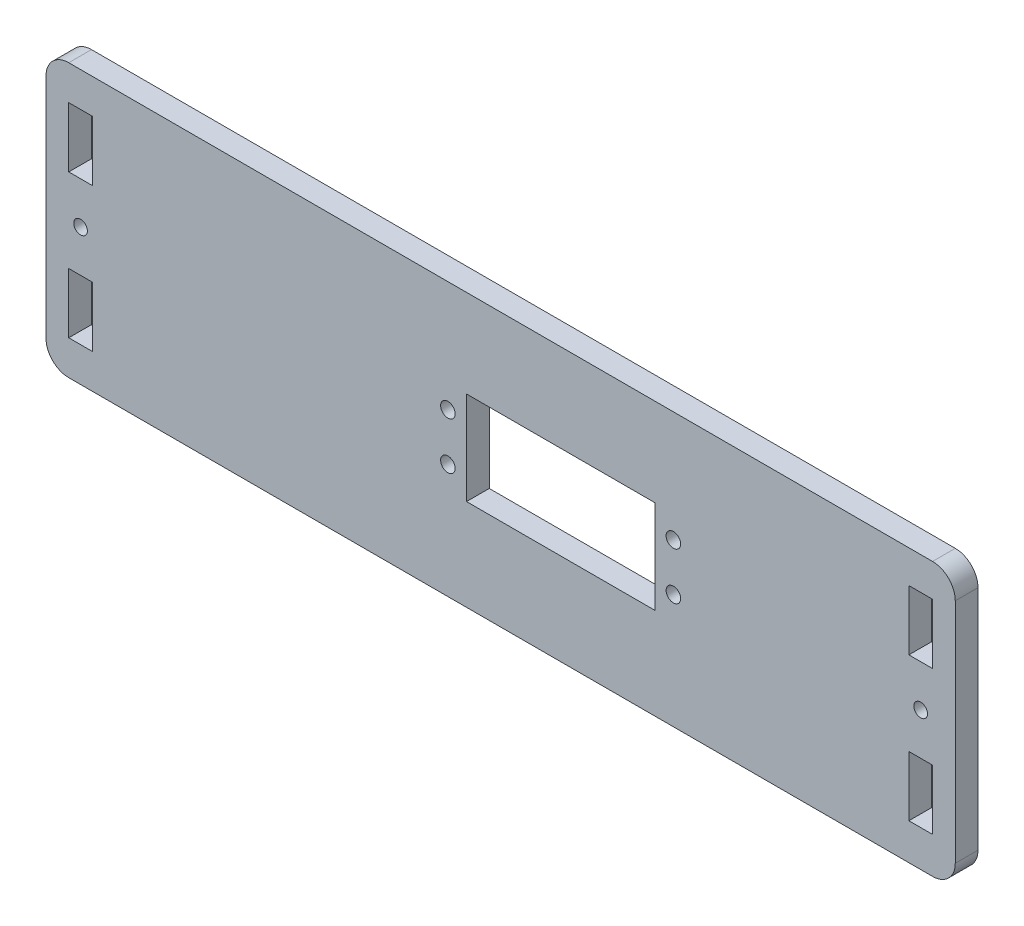
SolidWorks part; units mm, degrees
ref_plane "Front" through (0, 0, 0) normal (0, 0, 1) x (1, 0, 0)
ref_plane "Top" through (0, 0, 0) normal (0, 1, 0) x (1, 0, 0)
ref_plane "Right" through (0, 0, 0) normal (1, 0, 0) x (0, 0, -1)
sketch "Sketch1" plane through (0, 0, 0) normal (0, 0, 1) x (1, 0, 0)
  line L0 (-36.0276, 22.5737) -> (153.9724, 22.5737)
  line L1 (-33.4247, -16.6263) -> (-33.4247, 1.7737) construction
  line L2 (-41.0276, 17.5737) -> (-41.0276, -32.4263)
  line L4 (-30.8247, 1.7737) -> (-30.8247, 14.9737)
  line L12 (158.9724, 17.5737) -> (158.9724, -32.4263)
  line L13 (153.9694, -29.4263) -> (148.7694, -29.4263)
  line L14 (148.7694, -29.4263) -> (148.7694, -16.2263)
  line L15 (148.7694, 2.1737) -> (148.7694, 15.3737)
  line L16 (153.9694, 15.3737) -> (153.9694, 2.1737)
  line L17 (153.9694, -16.2263) -> (148.7694, -16.2263)
  line L18 (-36.0276, -37.4263) -> (153.9724, -37.4263)
  line L19 (153.9694, -16.2263) -> (153.9694, -29.4263)
  line L20 (51.4724, 3.2237) -> (92.8724, 3.2237)
  line L21 (51.4724, 3.2237) -> (51.4724, -17.2763)
  line L22 (51.4724, -17.2763) -> (92.8724, -17.2763)
  line L23 (92.8724, 3.2237) -> (92.8724, -17.2763)
  line L24 (92.8724, -7.0263) -> (85.3724, -7.0263) construction
  line L25 (58.9724, 22.5737) -> (58.9724, -37.4263) construction
  line L26 (51.4724, -7.0263) -> (58.9724, -7.0263) construction
  line L27 (153.9694, 15.3737) -> (148.7694, 15.3737)
  line L28 (153.9694, 2.1737) -> (148.7694, 2.1737)
  line L29 (151.3694, -7.0263) -> (158.9724, -7.0263) construction
  line L30 (151.3694, -16.2263) -> (151.3694, 2.1737) construction
  line L31 (-33.4247, -7.4263) -> (-41.0276, -7.4263) construction
  line L32 (-36.0247, 1.7737) -> (-30.8247, 1.7737)
  line L33 (-36.0247, 14.9737) -> (-30.8247, 14.9737)
  line L34 (-36.0247, -16.6263) -> (-36.0247, -29.8263)
  line L35 (-36.0247, -16.6263) -> (-30.8247, -16.6263)
  line L36 (-36.0247, 14.9737) -> (-36.0247, 1.7737)
  line L37 (-30.8247, -29.8263) -> (-30.8247, -16.6263)
  line L38 (-36.0247, -29.8263) -> (-30.8247, -29.8263)
  circle A0 centre (47.3724, -1.8264) radius 1.6
  circle A1 centre (47.3724, -12.2264) radius 1.6
  circle A2 centre (96.9724, -12.2264) radius 1.6
  circle A3 centre (96.9724, -1.8264) radius 1.6
  arc A4 (153.9724, 22.5737) -> (158.9724, 17.5737) centre (153.9724, 17.5737) cw
  circle A5 centre (151.3694, -7.0263) radius 1.5
  circle A6 centre (-33.4247, -7.4263) radius 1.5
  arc A7 (153.9724, -37.4263) -> (158.9724, -32.4263) centre (153.9724, -32.4263) ccw
  arc A8 (-41.0276, -32.4263) -> (-36.0276, -37.4263) centre (-36.0276, -32.4263) ccw
  arc A9 (-36.0276, 22.5737) -> (-41.0276, 17.5737) centre (-36.0276, 17.5737) ccw
  dimension "D1" = 5
extrude "Boss-Extrude1" add sketch "Sketch1" along normal blind 5
